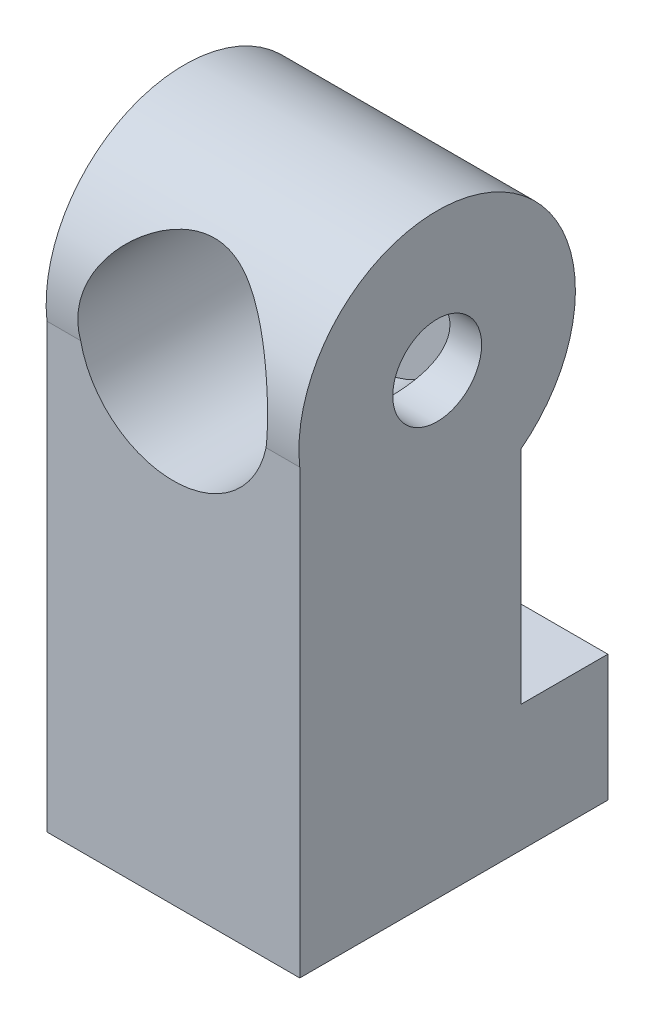
SolidWorks part; units mm, degrees
ref_plane "Front Plane" through (0, 0, 0) normal (0, 0, 1) x (1, 0, 0)
ref_plane "Top Plane" through (0, 0, 0) normal (0, 1, 0) x (1, 0, 0)
ref_plane "Right Plane" through (0, 0, 0) normal (1, 0, 0) x (0, 0, -1)
sketch "Sketch1" plane through (0, 0, 0) normal (1, 0, 0) x (0, 0, -1)
  line L0 (0, 0) -> (7.8, 0)
  line L1 (7.8, 0) -> (7.8, 3.2)
  line L2 (7.8, 3.2) -> (5.6, 3.2)
  line L3 (5.6, 3.2) -> (5.6, 8.8)
  line L4 (0, 11.2) -> (0, 0)
  arc A1 (5.6, 8.8) -> (0, 11.2) centre (3.4789, 11.584) ccw
  dimension "D4" = 5.6
  dimension "D5" = 7
  dimension "D6" = 2.2
  dimension "D1" = 7.8
  dimension "D2" = 11.2
  dimension "D3" = 3.2
extrude "Boss-Extrude1" add sketch "Sketch1" along normal blind 6.4
sketch "Sketch2" plane through (6.4, 0, 0) normal (1, 0, 0) x (0, 0, -1)
  circle A0 centre (3.4789, 11.584) radius 1.125
  dimension "D1" = 2.25
extrude "Cut-Extrude1" cut sketch "Sketch2" against normal blind 2
sketch "Sketch4" plane through (0, 0, 0) normal (0, 0, 1) x (1, 0, 0)
  line L0 (6.4, 0) -> (0, 0) construction
  circle A0 centre (3.2, 11.7) radius 2.4
  point P4 (3.2, 0)
  dimension "D1" = 4.8
  dimension "D2" = 11.7
extrude "Cut-Extrude3" cut sketch "Sketch4" against normal mid plane 10
sketch "Sketch5" plane through (0, 0, 0) normal (0, -1, 0) x (1, 0, 0)
  line L0 (6.4, 0) -> (0, 0) construction
  line L1 (5.6, -1.4) -> (0.8, -1.4)
  line L2 (5.6, -1.4) -> (5.6, -4.7)
  line L3 (5.6, -4.7) -> (0.8, -4.7)
  line L4 (0.8, -1.4) -> (0.8, -4.7)
  line L5 (5.6, -1.4) -> (0.8, -4.7) construction
  line L6 (5.6, -4.7) -> (0.8, -1.4) construction
  line L7 (0, 0) -> (0, -7.8) construction
  line L8 (6.4, 0) -> (6.4, -7.8) construction
  point P0 (3.2, -3.05)
  dimension "D1" = 3.3
  dimension "D2" = 4.8
  dimension "D3" = 1.4
  dimension "D4" = 0.8
  dimension "D5" = 0.8
extrude "Cut-Extrude4" cut sketch "Sketch5" against normal blind 8.9
ref_plane "Plane1" through (0, 0, 10) normal (0, 0, 1) x (1, 0, 0)
mirror "Mirror1" [suppressed] about plane through (0, 0, 10) normal (0, 0, 1)
pattern_linear "LPattern1" [suppressed] count 2 spacing 50
